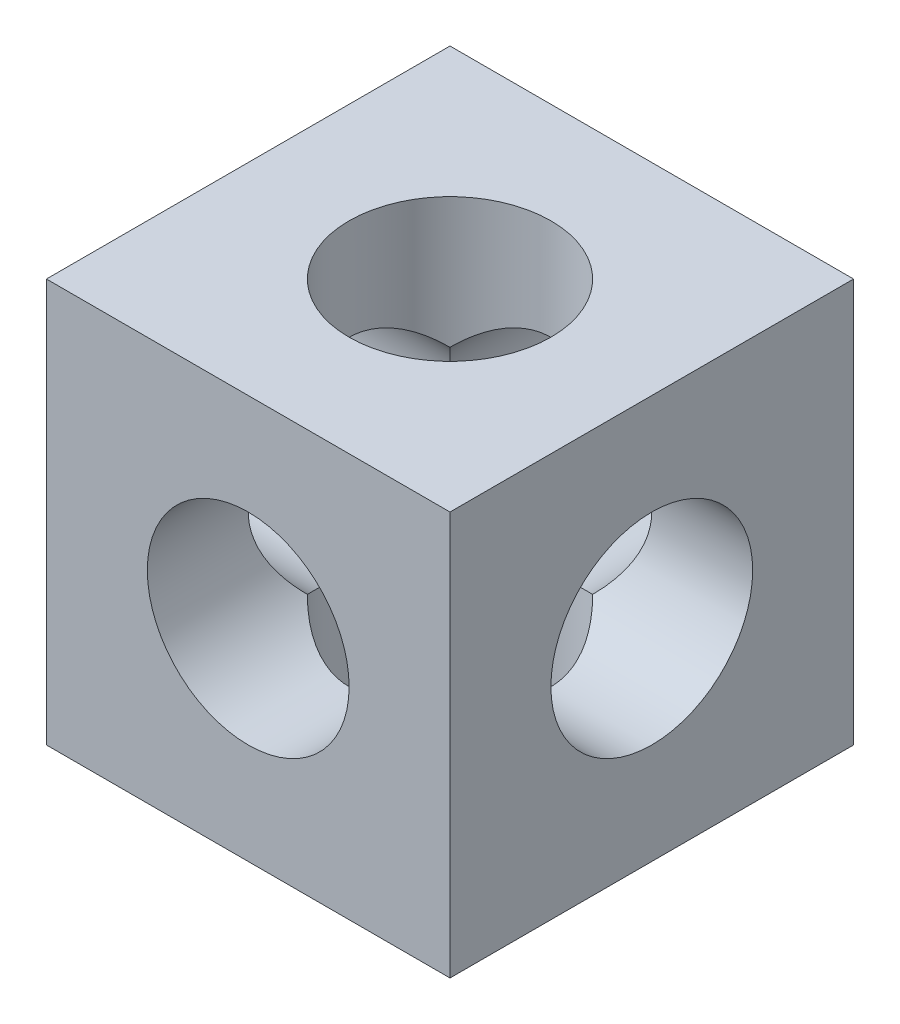
SolidWorks part; units mm, degrees
ref_plane "Front Plane" through (0, 0, 0) normal (0, 0, 1) x (1, 0, 0)
ref_plane "Top Plane" through (0, 0, 0) normal (0, 1, 0) x (1, 0, 0)
ref_plane "Right Plane" through (0, 0, 0) normal (1, 0, 0) x (0, 0, -1)
sketch "Sketch1" plane through (0, 0, 0) normal (0, 1, 0) x (1, 0, 0)
  line L1 (-25.4, -25.4) -> (25.4, -25.4)
  line L2 (-25.4, -25.4) -> (-25.4, 25.4)
  line L3 (-25.4, 25.4) -> (25.4, 25.4)
  line L4 (25.4, -25.4) -> (25.4, 25.4)
  line L5 (-25.4, -25.4) -> (25.4, 25.4) construction
  line L6 (-25.4, 25.4) -> (25.4, -25.4) construction
  point P0 (0, 0)
  dimension "D1" = 50.8
extrude "Boss-Extrude1" add sketch "Sketch1" along normal blind 50.8
sketch "Sketch2" plane through (0, 0, 25.4) normal (0, 0, 1) x (1, 0, 0)
  line L0 (0, 38.1) -> (0, 12.7) construction
  line L1 (-12.7, 25.4) -> (12.7, 25.4) construction
  line L2 (-25.4, 50.8) -> (25.4, 50.8) construction
  line L3 (-25.4, 0) -> (25.4, 0) construction
  line L4 (-25.4, 50.8) -> (-25.4, 0) construction
  line L5 (25.4, 50.8) -> (25.4, 0) construction
  circle A0 centre (0, 25.4) radius 12.7
  dimension "D1" = 25.4
extrude "Cut-Extrude1" cut sketch "Sketch2" against normal through all
sketch "Sketch3" plane through (25.4, 0, 0) normal (1, 0, 0) x (0, 0, -1)
  line L0 (0, 38.1) -> (0, 12.7) construction
  line L1 (-12.7, 25.4) -> (12.7, 25.4) construction
  line L2 (-25.4, 50.8) -> (-25.4, 0) construction
  line L3 (25.4, 50.8) -> (25.4, 0) construction
  line L4 (-25.4, 50.8) -> (25.4, 50.8) construction
  line L5 (-25.4, 0) -> (25.4, 0) construction
  circle A0 centre (0, 25.4) radius 12.7
  dimension "D1" = 25.4
extrude "Cut-Extrude2" cut sketch "Sketch3" against normal through all
sketch "Sketch4" plane through (0, 50.8, 0) normal (0, 1, 0) x (1, 0, 0)
  circle A0 centre (0, 0) radius 12.7
  dimension "D1" = 25.4
extrude "Cut-Extrude3" cut sketch "Sketch4" against normal through all
